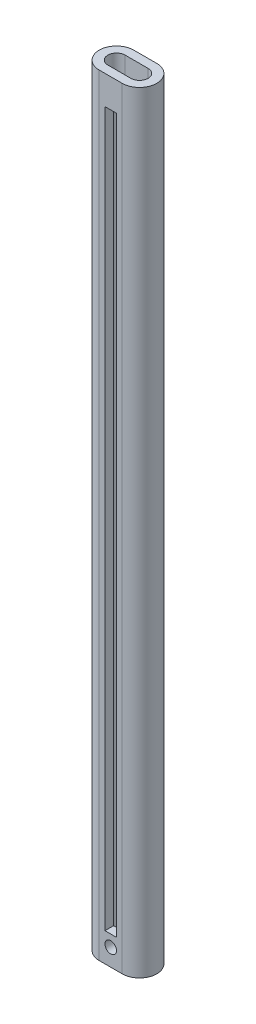
SolidWorks part; units mm, degrees
ref_plane "Alzado" through (0, 0, 0) normal (0, 0, 1) x (1, 0, 0)
ref_plane "Planta" through (0, 0, 0) normal (0, 1, 0) x (1, 0, 0)
ref_plane "Vista lateral" through (0, 0, 0) normal (1, 0, 0) x (0, 0, -1)
sketch "Croquis1" plane through (0, 0, 0) normal (0, 1, 0) x (1, 0, 0)
  line L0 (0, -1000) -> (0, -1.5) construction
  line L1 (-1000, 0) -> (0.5, 0) construction
  line L3 (0, 1.5) -> (2, 1.5)
  line L6 (2, -1.5) -> (1, -1.5)
  line L7 (-1, -1.5) -> (-2, -1.5)
  line L9 (-2, 1.5) -> (0, 1.5)
  line L10 (-2, -3) -> (-1, -3)
  line L11 (3.5, 0) -> (1004.9932, 0) construction
  line L12 (0, 3) -> (5, 3)
  line L16 (-5, 3) -> (0, 3)
  line L17 (-5, 3) -> (-5, -3)
  line L18 (-5, -3) -> (5, -3)
  line L19 (5, -3) -> (5, 3)
  line L20 (0, 3) -> (0, 1005.4325) construction
  line L21 (-1, -3) -> (-1, -1.5)
  line L22 (2, -3) -> (1, -3)
  line L23 (1, -3) -> (1, -1.5)
  line L24 (2, 1.5) -> (2, -1.5)
  line L25 (-2, 1.5) -> (-2, -1.5)
  arc A4 (-2, 1.5) -> (-2, -1.5) centre (-2, 0) ccw
  arc A6 (2, -1.5) -> (2, 1.5) centre (2, 0) ccw
  arc A7 (-2, 1.5) -> (-2, -1.5) centre (-2, 0) ccw
  arc A8 (-2, 3) -> (-2, -3) centre (-2, 0) ccw
  arc A10 (2, -3) -> (2, 3) centre (2, 0) ccw
  dimension "D5" = 3
  dimension "D10" = 2
  dimension "D4" = 3
  dimension "D1" = 3
  dimension "D2" = 3
  dimension "D3" = 1.5
  dimension "D8" = 2
  dimension "D9" = 2
extrude "Saliente-Extruir1" add sketch "Croquis1" against normal blind 124
sketch "Croquis2" plane through (0, 0, 0) normal (0, 1, 0) x (1, 0, 0)
  line L0 (-1, -1.5) -> (1, -1.5)
  line L1 (1, -1.5) -> (1, -3)
  line L2 (1, -3) -> (-1, -3)
  line L3 (-1, -3) -> (-1, -1.5)
sketch "Croquis7" plane through (0, 0, 0) normal (0, 1, 0) x (1, 0, 0)
  line L0 (-1, -1.5) -> (-2, -1.5)
  line L2 (-2, -1.5) -> (-2, -3)
  line L3 (-2, -3) -> (-1, -3)
  line L4 (-2, 1.5) -> (-2, 3)
  line L5 (-2, 1.5) -> (2, 1.5) construction
  line L6 (-2, 3) -> (2, 3)
  line L7 (2, 3) -> (2, 1.5)
  line L8 (2, 1.5) -> (-2, 1.5)
  line L9 (-1, -3) -> (1, -3)
  line L10 (1, -3) -> (1, -1.5)
  line L11 (1, -1.5) -> (-1, -1.5)
  line L12 (2, -1.5) -> (1, -1.5) construction
  line L13 (2, -1.5) -> (1, -1.5)
  arc A0 (-2, 1.5) -> (-2, -1.5) centre (-2, 0) ccw construction
  arc A1 (2, -1.5) -> (2, 1.5) centre (2, 0) ccw construction
  arc A2 (2, -1.5) -> (2, 1.5) centre (2, 0) ccw
  arc A3 (-2, 1.5) -> (-2, -1.5) centre (-2, 0) ccw
  line M1 (1, -3) -> (2, -3)
  arc M2 (2, -3) -> (2, 3) centre (2, 0) ccw
  line M3 (2, 3) -> (-2, 3)
  arc M4 (-2, 3) -> (-2, -3) centre (-2, 0) ccw
  line M5 (-2, -3) -> (-1, -3)
  line M6 (-1, -3) -> (-1, -1.5)
  line M7 (-1, -1.5) -> (-2, -1.5)
  arc M8 (-2, -1.5) -> (-2, 1.5) centre (-2, 0) cw
  line M9 (-2, 1.5) -> (2, 1.5)
  arc M10 (2, 1.5) -> (2, -1.5) centre (2, 0) cw
  line M11 (2, -1.5) -> (1, -1.5)
  line M12 (1, -1.5) -> (1, -3)
extrude "Saliente-Extruir3" add sketch "Croquis7" along normal blind 5 contours L7 L4 M3 M9 | L4 L2 M8 M4 | L11 L9 M12 M6 | L2 M7 M5 M6 | L7 M2 M10 M11 M12 M1
sketch "Croquis8" plane through (0, -124, 0) normal (0, -1, 0) x (1, 0, 0)
  line L0 (-1, 3) -> (1, 3)
  line L1 (1, 3) -> (1, 1.5)
  line L2 (1, 1.5) -> (-1, 1.5)
  line L3 (-2, -3) -> (-2, -1.5)
  line L4 (-2, -1.5) -> (2, -1.5)
  line L5 (-2, -1.5) -> (2, -1.5) construction
  line L6 (2, -1.5) -> (2, -3)
  line L7 (2, -3) -> (-2, -3)
  arc A0 (2, -1.5) -> (2, 1.5) centre (2, 0) ccw construction
  line M1 (2, 3) -> (1, 3)
  line M2 (1, 3) -> (1, 1.5)
  line M3 (1, 1.5) -> (2, 1.5)
  arc M4 (2, 1.5) -> (2, -1.5) centre (2, 0) cw
  line M5 (2, -1.5) -> (-2, -1.5)
  arc M6 (-2, -1.5) -> (-2, 1.5) centre (-2, 0) cw
  line M7 (-2, 1.5) -> (-1, 1.5)
  line M8 (-1, 1.5) -> (-1, 3)
  line M9 (-1, 3) -> (-2, 3)
  arc M10 (-2, 3) -> (-2, -3) centre (-2, 0) ccw
  line M11 (-2, -3) -> (2, -3)
  arc M12 (2, -3) -> (2, 3) centre (2, 0) ccw
extrude "Saliente-Extruir4" add sketch "Croquis8" along normal blind 5 contours L3 M10 M6 M7 M8 M9 | L2 L0 M2 M8 | L6 M4 M12 M1 M2 M3 | L6 L3 M5 M11
sketch "Croquis9" plane through (0, 0, 3) normal (0, 0, 1) x (1, 0, 0)
  line L0 (2, -129) -> (-2, -129) construction
  circle A0 centre (0, -126) radius 1
  dimension "D1" = 3
extrude "Cortar-Extruir1" cut sketch "Croquis9" against normal through all both and the other way through all
